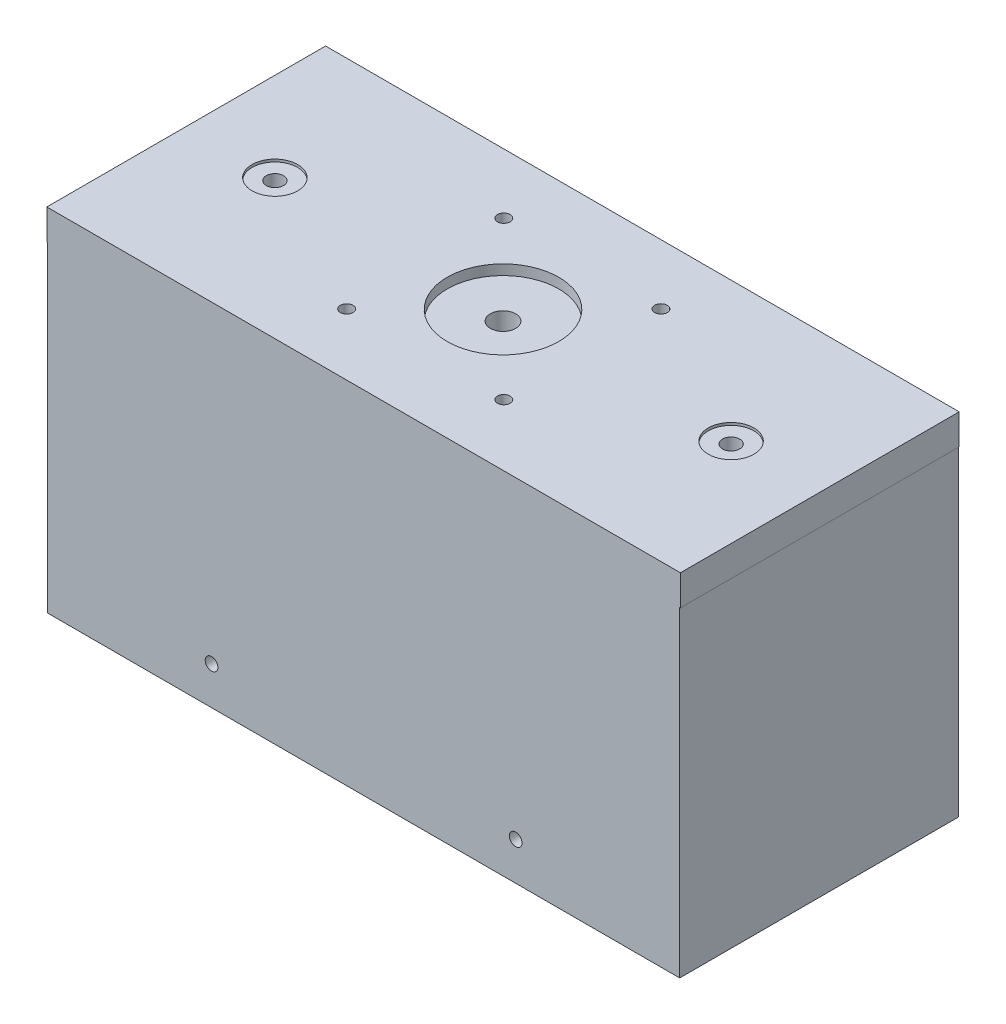
SolidWorks part; units mm, degrees
ref_plane "前视基准面" through (0, 0, 0) normal (0, 0, 1) x (1, 0, 0)
ref_plane "上视基准面" through (0, 0, 0) normal (0, 1, 0) x (1, 0, 0)
ref_plane "右视基准面" through (0, 0, 0) normal (1, 0, 0) x (0, 0, -1)
sketch "草图1" plane through (0, 0, 0) normal (0, 1, 0) x (1, 0, 0)
  line L1 (-62.5, 27.5) -> (62.5, 27.5)
  line L2 (-62.5, 27.5) -> (-62.5, -27.5)
  line L3 (-62.5, -27.5) -> (62.5, -27.5)
  line L4 (62.5, 27.5) -> (62.5, -27.5)
  line L5 (-62.5, 27.5) -> (62.5, -27.5) construction
  line L6 (-62.5, -27.5) -> (62.5, 27.5) construction
  point P0 (0, 0)
  dimension "D1" = 125
  dimension "D2" = 55
extrude "凸台-拉伸1" add sketch "草图1" along normal blind 6
sketch "草图2" plane through (0, 6, 0) normal (0, 1, 0) x (1, 0, 0)
  circle A0 centre (0, 0) radius 11
  dimension "D1" = 22
extrude "切除-拉伸1" cut sketch "草图2" against normal blind 2
sketch "草图3" plane through (0, 4, 0) normal (0, 1, 0) x (1, 0, 0)
  circle A0 centre (0, 0) radius 2.5
  dimension "D1" = 5
extrude "切除-拉伸2" cut sketch "草图3" against normal up to next
hole_wizard "M3 螺纹孔1" positions "草图4" profile "草图5" tap size "M3" standard "GB"
sketch "草图4" plane through (0, 6, 0) normal (0, 1, 0) x (1, 0, 0)
  point P0 (15.5, 15.6574)
  point P3 (15.5, -15.3426)
  point P6 (-15.5, -15.3426)
  point P9 (-15.5, 15.6574)
sketch "草图5" plane through (15.5, 6, -15.6574) normal (1, 0, 0) x (0, 0, 1)
  line L0 (0, 0) -> (0, 8.2511)
  line L1 (0, 8.2511) -> (1.25, 7.5)
  line L2 (1.25, 7.5) -> (1.25, 0)
  line L5 (1.25, 0) -> (0, 0)
  line L10 (0, 8.2511) -> (-1.25, 7.5) construction
  line L11 (0, -6.35) -> (0, 107.95) construction
  dimension "螺纹孔钻头直径" = 2.5
  dimension "螺纹孔钻头深度" = 7.5
  dimension "导头角度" = 118
cosmetic thread "孔螺蚊线11" parameters "D1"=6, "D2"=3.5
cosmetic thread "孔螺蚊线14" parameters "D1"=6, "D2"=3.5
cosmetic thread "孔螺蚊线15" parameters "D1"=6, "D2"=3.5
cosmetic thread "孔螺蚊线16" parameters "D1"=6, "D2"=3.5
sketch "草图6" plane through (0, 0, 0) normal (0, -1, 0) x (1, 0, 0)
  line L0 (-62.5, 27.5) -> (62.5, 27.5) construction
  line L1 (60, -24.8426) -> (-60, -24.8426)
  line L2 (60, -24.8426) -> (60, 24.8426)
  line L3 (60, 24.8426) -> (-60, 24.8426)
  line L4 (-60, -24.8426) -> (-60, 24.8426)
  line L5 (60, -24.8426) -> (-60, 24.8426) construction
  line L6 (60, 24.8426) -> (-60, -24.8426) construction
  line L7 (62.362, -27.5) -> (-62.362, -27.5)
  line L8 (62.362, -27.5) -> (62.362, 27.5)
  line L9 (62.362, 27.5) -> (-62.362, 27.5)
  line L10 (-62.362, -27.5) -> (-62.362, 27.5)
  line L11 (62.362, -27.5) -> (-62.362, 27.5) construction
  line L12 (62.362, 27.5) -> (-62.362, -27.5) construction
  point P0 (0, 0)
  point P7 (0, 0)
extrude "凸台-拉伸2" add sketch "草图6" along normal up to vertex (63.3064 mm away)
sketch "草图7" plane through (0, 0, -27.5) normal (0, 0, -1) x (-1, 0, 0)
  line L4 (-62.5, 6) -> (-62.5, 0)
  line L5 (-62.5, 0) -> (-62.362, 0)
  line L6 (62.5, 0) -> (62.5, 6)
  line L7 (62.5, 6) -> (-62.5, 6)
  line L8 (-62.5, 6) -> (-62.5, 0)
  line L10 (62.5, 0) -> (62.5, 6)
  line L11 (62.5, 6) -> (-62.5, 6)
  line L16 (-62.5, 0) -> (-62.362, 0)
  line L38 (-62.362, -63.3064) -> (62.362, -63.3064)
  line L42 (-62.362, -63.3064) -> (62.362, -63.3064)
  line L45 (-62.362, 0) -> (-62.362, -63.3064)
  line L47 (-62.362, 0) -> (-62.362, -63.3064)
  line L49 (62.362, -63.3064) -> (62.362, 0)
  line L50 (62.362, -63.3064) -> (62.362, 0)
  line L51 (62.362, 0) -> (62.5, 0)
  line L52 (62.362, 0) -> (62.5, 0)
  circle A0 centre (30, -55.8064) radius 1.25 construction
  circle A1 centre (-30, -55.8064) radius 1.25 construction
  circle A2 centre (30, -55.8064) radius 1.25
  circle A3 centre (-30, -55.8064) radius 1.25
  dimension "D1" = 0
hole_wizard "M3 螺纹孔2" positions "草图8" profile "草图9" tap size "M3" standard "GB"
sketch "草图8" plane through (0, 0, -27.5) normal (0, 0, -1) x (-1, 0, 0)
  point P0 (30, -55.8064)
  point P3 (-30, -55.8064)
sketch "草图9" plane through (-30, -55.8064, -27.5) normal (1, 0, 0) x (0, 1, 0)
  line L0 (0, 0) -> (0, 2.6574)
  line L1 (0, 2.6574) -> (1.25, 2.6574)
  line L2 (1.25, 2.6574) -> (1.25, 0)
  line L5 (1.25, 0) -> (0, 0)
  line L11 (0, -6.35) -> (0, 107.95) construction
  dimension "通孔螺纹孔钻头直径" = 2.5
  dimension "通孔螺纹孔钻头深度" = 2.6574
cosmetic thread "孔螺蚊线5" parameters "D2"=3
cosmetic thread "孔螺蚊线6" parameters "D2"=3
hole_wizard "M3 螺纹孔3" positions "草图11" profile "草图12" tap size "M3" standard "GB" end condition up to next
sketch "草图11" plane through (0, 0, 27.5) normal (0, 0, 1) x (1, 0, 0)
  point P0 (30, -55.8064)
  point P3 (-30, -55.8064)
sketch "草图12" plane through (30, -55.8064, 27.5) normal (1, 0, 0) x (0, -1, 0)
  line L0 (0, 0) -> (0, 2.6574)
  line L1 (0, 2.6574) -> (1.25, 2.6574)
  line L2 (1.25, 2.6574) -> (1.25, 0)
  line L5 (1.25, 0) -> (0, 0)
  line L11 (0, -6.35) -> (0, 107.95) construction
  dimension "通孔螺纹孔钻头直径" = 2.5
  dimension "通孔螺纹孔钻头深度" = 2.6574
cosmetic thread "孔螺蚊线7" parameters "D2"=3
cosmetic thread "孔螺蚊线17" parameters "D2"=3
sketch "草图13" plane through (0, 6, 0) normal (0, 1, 0) x (1, 0, 0)
  line L0 (0, 0) -> (45, 0) construction
  line L1 (0, 0) -> (-45, 0) construction
  circle A0 centre (-45, 0) radius 7.9824 construction
  circle A1 centre (45, 0) radius 7.9824 construction
  dimension "D1" = 90
  dimension "D2" = 45
hole_wizard "M3 六角头螺栓的柱形沉头孔1" positions "3D草图1" profile "草图14" counterbore size "M3" standard "GB"
sketch3d "3D草图1"
  point P0 (-45, 6, 0)
  point P3 (45, 6, 0)
sketch "草图14" plane through (-45, 6, 0) normal (1, 0, 0) x (0, 0, 1)
  line L0 (0, 0) -> (0, 6.0215)
  line L1 (0, 6.0215) -> (1.7, 5)
  line L2 (1.7, 5) -> (1.7, 0.5)
  line L3 (1.7, 0.5) -> (4.5, 0.5)
  line L4 (4.5, 0.5) -> (4.5, 0)
  line L5 (4.5, 0) -> (0, 0)
  line L10 (0, 6.0215) -> (-1.7, 5) construction
  line L11 (0, -6.35) -> (0, 107.95) construction
  dimension "孔直径" = 3.4
  dimension "孔深度" = 5
  dimension "柱形沉头孔直径" = 9
  dimension "柱形沉头孔深度" = 0.5
  dimension "导头角度" = 118
